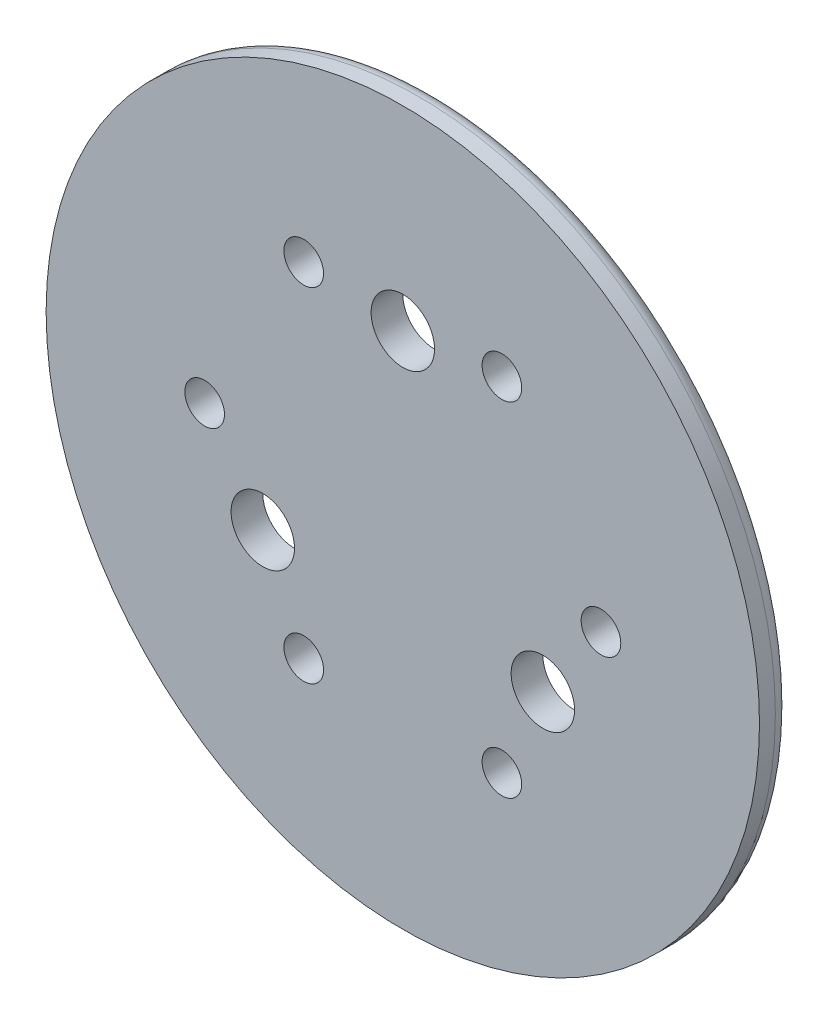
SolidWorks part; units mm, degrees
ref_plane "前视基准面" through (0, 0, 0) normal (0, 0, 1) x (1, 0, 0)
ref_plane "上视基准面" through (0, 0, 0) normal (0, 1, 0) x (1, 0, 0)
ref_plane "右视基准面" through (0, 0, 0) normal (1, 0, 0) x (0, 0, -1)
other "Configuration Table"
sketch "草图1" plane through (0, 0, 0) normal (0, 0, 1) x (1, 0, 0)
  line L0 (0, 0) -> (0, 10.2) construction
  line L1 (0, 0) -> (-6.25, 10.8253) construction
  line L2 (0, 0) -> (6.25, 10.8253) construction
  line L3 (0, 0) -> (12.5, 0) construction
  line L4 (0, 0) -> (6.25, -10.8253) construction
  line L5 (0, 0) -> (-6.25, -10.8253) construction
  line L6 (0, 0) -> (-12.5, 0) construction
  line L7 (0, 0) -> (-8.8335, -5.1) construction
  line L8 (0, 0) -> (8.8335, -5.1) construction
  circle A0 centre (0, 0) radius 22.5
  circle A1 centre (0, 0) radius 12.5 construction
  circle A2 centre (0, 10.2) radius 2
  circle A3 centre (-6.25, 10.8253) radius 1.25
  circle A4 centre (6.25, 10.8253) radius 1.25
  circle A5 centre (12.5, 0) radius 1.25
  circle A6 centre (6.25, -10.8253) radius 1.25
  circle A7 centre (-6.25, -10.8253) radius 1.25
  circle A8 centre (-12.5, 0) radius 1.25
  circle A9 centre (-8.8335, -5.1) radius 2
  circle A10 centre (8.8335, -5.1) radius 2
  dimension "D1" = 45
  dimension "D2" = 25
  dimension "D4" = 4
  dimension "D6" = 2.5
  dimension "D7" = 60
  dimension "D8" = 2.5
  dimension "D14" = 2.5
  dimension "D15" = 2.5
  dimension "D16" = 2.5
  dimension "D17" = 2.5
  dimension "D23" = 4
  dimension "D24" = 4
  dimension "D3" = 10.2
  dimension "D5" = 30
  dimension "D9" = 60
  dimension "D10" = 60
  dimension "D11" = 60
  dimension "D12" = 60
  dimension "D13" = 60
  dimension "D18" = 10.2
  dimension "D19" = 10.2
  dimension "D20" = 120
  dimension "D21" = 120
  dimension "D22" = 120
extrude "凸台-拉伸1" add sketch "草图1" along normal blind 2
fillet "圆角1" radius 1 1 edges at (22.5, 0, 0)
